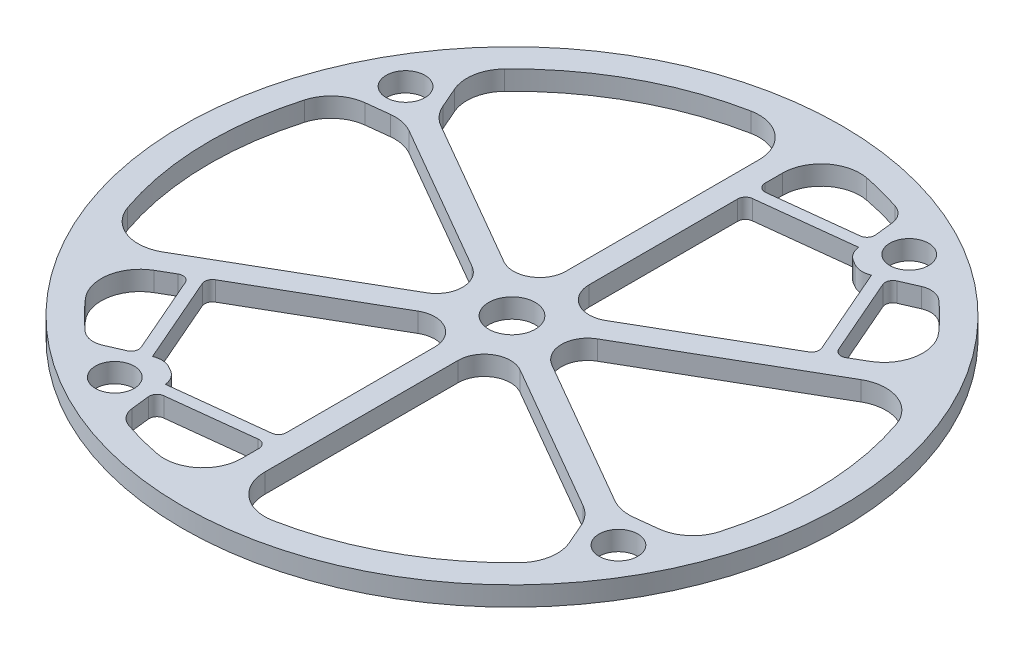
SolidWorks part; units mm, degrees
material "6063-T6"
ref_plane "Płaszczyzna przednia" through (0, 0, 0) normal (0, 0, 1) x (1, 0, 0)
ref_plane "Płaszczyzna górna" through (0, 0, 0) normal (0, 1, 0) x (1, 0, 0)
ref_plane "Płaszczyzna prawa" through (0, 0, 0) normal (1, 0, 0) x (0, 0, -1)
sketch "Szkic1" plane through (0, 0, 0) normal (0, 1, 0) x (1, 0, 0)
  circle A0 centre (0, 0) radius 85
  dimension "D1" = 170
extrude "Dodanie-wyciągnięcie1" add sketch "Szkic1" along normal blind 5
sketch "Szkic2" plane through (0, 5, 0) normal (0, 1, 0) x (1, 0, 0)
  line L0 (0, 0) -> (0, 85) construction
  line L1 (0, 85) -> (0, 75) construction
  line L2 (0, 64.5631) -> (3, 64.5631) construction
  line L3 (0, 64.5631) -> (-3, 64.5631) construction
  line L4 (3, 64.5631) -> (3, 9.5394)
  line L5 (-3, 64.5631) -> (-3, 9.5394)
  line L6 (-3, 64.5631) -> (-3, 77.9423) construction
  line L7 (3, 64.5631) -> (3, 77.9423) construction
  line L8 (3, 64.5631) -> (3, 77.9423)
  line L9 (-3, 77.9423) -> (-3, 64.5631)
  line L10 (57.4133, 29.6835) -> (69, 36.3731)
  line L11 (66, 41.5692) -> (54.4133, 34.8796)
  line L12 (54.4133, 34.8796) -> (6.7614, 7.3678)
  line L13 (57.4133, 29.6835) -> (9.7614, 2.1716)
  line L14 (-64.9519, 37.5) -> (0, 0) construction
  line L15 (-54.4133, 34.8796) -> (-59.2452, 45.9892)
  line L16 (57.4133, -29.6835) -> (9.7614, -2.1716)
  line L17 (54.4133, -34.8796) -> (6.7614, -7.3678)
  line L18 (-3, -64.5631) -> (-3, -77.9423)
  line L19 (3, -77.9423) -> (3, -64.5631)
  line L20 (3, -64.5631) -> (3, -9.5394)
  line L21 (-3, -64.5631) -> (-3, -9.5394)
  line L22 (-57.4133, -29.6835) -> (-69, -36.3731)
  line L23 (-66, -41.5692) -> (-54.4133, -34.8796)
  line L24 (-54.4133, -34.8796) -> (-6.7614, -7.3678)
  line L25 (-57.4133, -29.6835) -> (-9.7614, -2.1716)
  line L26 (-59.2452, 45.9892) -> (-60.6013, 49.1069)
  line L27 (-57.4133, 29.6835) -> (-69.4504, 28.3133)
  line L28 (-57.4133, 29.6835) -> (-9.7614, 2.1716)
  line L29 (-54.4133, 34.8796) -> (-6.7614, 7.3678)
  line L30 (39, 67.55) -> (0, 0) construction
  line L31 (39, 67.55) -> (42.5, 73.6122) construction
  line L32 (42.5, 73.6122) -> (37.5, 64.9519) construction
  line L33 (-54.4133, 34.8796) -> (-66, 41.5692) [skipped]
  line L34 (-69, 36.3731) -> (-57.4133, 29.6835) [skipped]
  line L35 (69, -36.3731) -> (57.4133, -29.6835) [skipped]
  line L36 (54.4133, -34.8796) -> (66, -41.5692) [skipped]
  line L37 (-69.4504, 28.3133) -> (-72.8284, 27.9288)
  line L38 (34.8796, 54.4133) -> (45.9892, 59.2452)
  line L39 (45.9892, 59.2452) -> (49.1069, 60.6013)
  line L40 (29.6835, 57.4133) -> (28.3133, 69.4504)
  line L41 (28.3133, 69.4504) -> (27.9288, 72.8284)
  line L42 (54.4133, -34.8796) -> (59.2452, -45.9892)
  line L43 (59.2452, -45.9892) -> (60.6013, -49.1069)
  line L44 (57.4133, -29.6835) -> (69.4504, -28.3133)
  line L45 (69.4504, -28.3133) -> (72.8284, -27.9288)
  line L46 (-34.8796, -54.4133) -> (-45.9892, -59.2452)
  line L47 (-45.9892, -59.2452) -> (-49.1069, -60.6013)
  line L48 (-29.6835, -57.4133) -> (-28.3133, -69.4504)
  line L49 (-28.3133, -69.4504) -> (-27.9288, -72.8284)
  circle A0 centre (0, 0) radius 85 construction
  circle A2 centre (0, 0) radius 10
  circle A3 centre (0, 0) radius 78 construction
  circle A4 centre (64.9519, -37.5) radius 5
  circle A5 centre (-37.5, -64.9519) radius 5
  circle A6 centre (-64.9519, 37.5) radius 5
  arc A7 (-57.4133, 29.6835) -> (-54.4133, 34.8796) centre (0, 0) cw
  circle A8 centre (0, 0) radius 75 construction
  arc A9 (-64.9519, 37.5) -> (-62.309, 41.7444) centre (0, 0) cw construction
  circle A10 centre (37.5, 64.9519) radius 5
  arc A11 (-62.309, 41.7444) -> (-59.2452, 45.9892) centre (0, 0) cw
  arc A12 (-64.9519, 37.5) -> (-67.3062, 33.0889) centre (0, 0) ccw construction
  arc A13 (-67.3062, 33.0889) -> (-69.4504, 28.3133) centre (0, 0) ccw
  circle A14 centre (0, 0) radius 64.6327 construction
  arc A15 (-60.6013, 49.1069) -> (-3, 77.9423) centre (0, 0) cw
  circle A16 centre (9.7614, 16.9072) radius 6.7614 construction
  arc A17 (3, 16.9072) -> (13.142, 11.0517) centre (9.7614, 16.9072) ccw
  arc A18 (49.1069, 60.6013) -> (77.9423, 3) centre (0, 0) cw
  arc A19 (29.6835, 57.4133) -> (34.8796, 54.4133) centre (0, 0) cw
  arc A20 (60.6013, -49.1069) -> (3, -77.9423) centre (0, 0) cw
  arc A21 (57.4133, -29.6835) -> (54.4133, -34.8796) centre (0, 0) cw
  arc A22 (-49.1069, -60.6013) -> (-77.9423, -3) centre (0, 0) cw
  arc A23 (-29.6835, -57.4133) -> (-34.8796, -54.4133) centre (0, 0) cw
  arc A24 (-77.9423, -3) -> (-72.8284, 27.9288) centre (0, 0) cw
  arc A25 (-27.9288, -72.8284) -> (-3, -77.9423) centre (0, 0) ccw
  arc A26 (72.8284, -27.9288) -> (77.9423, 3) centre (0, 0) ccw
  arc A27 (3, 77.9423) -> (27.9288, 72.8284) centre (0, 0) cw
  circle A28 centre (0, 0) radius 6
  arc A29 (16.142, 5.8555) -> (16.142, -5.8555) centre (19.5227, 0) ccw
  arc A30 (13.142, -11.0517) -> (3, -16.9072) centre (9.7614, -16.9072) ccw
  arc A31 (-3, -16.9072) -> (-13.142, -11.0517) centre (-9.7614, -16.9072) ccw
  arc A32 (-16.142, -5.8555) -> (-16.142, 5.8555) centre (-19.5227, 0) ccw
  arc A33 (-13.142, 11.0517) -> (-3, 16.9072) centre (-9.7614, 16.9072) ccw
  point P55 (0, 0)
  point P60 (0, 0)
  point P61 (0, 0)
  point P66 (0, 0)
  point P85 (0, 0)
  point P93 (0, 0)
  point P101 (0, 0)
  point P117 (0, 0)
  dimension "D1" = 6
  dimension "D2" = 20
  dimension "D3" = 4
  dimension "D4" = 4
  dimension "D5" = 6
extrude "Wytnij-wyciągnięcie2" cut sketch "Szkic2" against normal blind 5 contours A15 L26 L15 L29 A2 L5 L9 | A27 L8 L4 A2 L12 L11 A18 L39 L38 A19 L40 L41 | L45 A26 A18 L10 L13 A2 L16 L44 | A20 L43 L42 L17 A2 L20 L19 | L49 A25 L18 L21 A2 L24 L23 A22 L47 L46 A23 L48 | A24 A22 L22 L25 A2 L28 L27 L37 | A6 | A28 | A10 | A4 | A5
fillet "Zaokrąglenie2" radius 10 12 edges at (-60.6013, 2.5, -49.1069) (-3, 2.5, -77.9423) (-69, 2.5, 36.3731) (-72.8284, 2.5, -27.9288) (69, 2.5, -36.3731) (72.8284, 2.5, 27.9288) (3, 2.5, -77.9423) (66, 2.5, -41.5692) (60.6013, 2.5, 49.1069) (3, 2.5, 77.9423) (-3, 2.5, 77.9423) (-66, 2.5, 41.5692)
fillet "Zaokrąglenie4" radius 10 4 edges at (54.4133, 2.5, 34.8796) (57.4133, 2.5, 29.6835) (-57.4133, 2.5, -29.6835) (-54.4133, 2.5, -34.8796)
fillet "Zaokrąglenie5" radius 5 8 edges at (-27.9288, 2.5, 72.8284) (-29.6835, 2.5, 57.4133) (-34.8796, 2.5, 54.4133) (-49.1069, 2.5, 60.6013) (27.9288, 2.5, -72.8284) (29.6835, 2.5, -57.4133) (34.8796, 2.5, -54.4133) (49.1069, 2.5, -60.6013)
sketch "Szkic3" plane through (0, 5, 0) normal (0, 1, 0) x (1, 0, 0)
  line L0 (0, 0) -> (0, 89.563) construction
  line L1 (0, 0) -> (110.8114, 0) construction
  line L2 (3, 57) -> (29.3886, 60.0037)
  line L3 (3, 16.9072) -> (3, 66.7458) construction
  line L4 (29.3889, 60.0012) -> (28.28, 69.7431) construction
  line L5 (3, 60.0194) -> (29.0493, 62.9845)
  line L6 (29.0493, 62.9845) -> (29.3886, 60.0037)
  line L7 (3, 60.0194) -> (3, 57)
  line L8 (0, 0) -> (37.5, 64.9519) construction
  line L9 (40.0215, 56.6497) -> (37.2705, 55.4531)
  line L10 (50.4783, 32.6078) -> (47.8634, 31.0981)
  line L11 (50.4783, 32.6078) -> (40.0215, 56.6497)
  line L12 (47.8634, 31.0981) -> (37.2705, 55.4531)
  line L13 (0, 0) -> (-64.9519, 37.5) construction
  line L14 (-47.8634, -31.0981) -> (-37.2705, -55.4531)
  line L15 (-50.4783, -32.6078) -> (-47.8634, -31.0981)
  line L16 (-40.0215, -56.6497) -> (-37.2705, -55.4531)
  line L17 (-50.4783, -32.6078) -> (-40.0215, -56.6497)
  line L18 (-3, -60.0194) -> (-3, -57)
  line L19 (-29.0493, -62.9845) -> (-29.3886, -60.0037)
  line L20 (-3, -57) -> (-29.3886, -60.0037)
  line L21 (-3, -60.0194) -> (-29.0493, -62.9845)
  dimension "D1" = 57
  dimension "D2" = 3
extrude "Dodanie-wyciągnięcie2" add sketch "Szkic3" against normal through all
fillet "Zaokrąglenie6" radius 2 12 edges at (3, 2.5, -57) (3, 2.5, -60.0194) (29.0493, 2.5, -62.9845) (40.0215, 2.5, -56.6497) (50.4783, 2.5, -32.6078) (47.8634, 2.5, -31.0981) (-50.4783, 2.5, 32.6078) (-47.8634, 2.5, 31.0981) (-40.0215, 2.5, 56.6497) (-3, 2.5, 60.0194) (-29.0493, 2.5, 62.9845) (-3, 2.5, 57)
